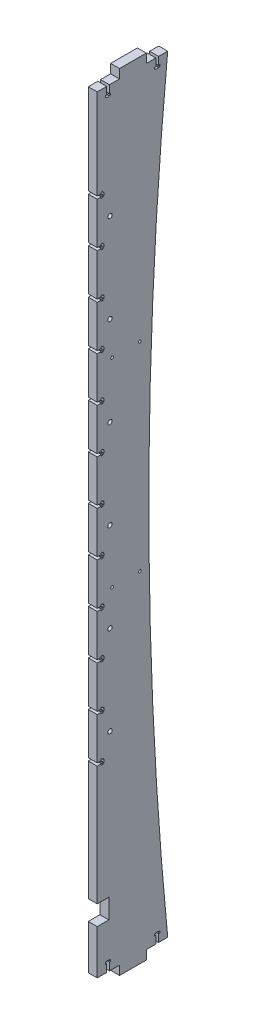
SolidWorks part; units mm, degrees
ref_plane "Płaszczyzna przednia" through (0, 0, 0) normal (0, 0, 1) x (1, 0, 0)
ref_plane "Płaszczyzna górna" through (0, 0, 0) normal (0, 1, 0) x (1, 0, 0)
ref_plane "Płaszczyzna prawa" through (0, 0, 0) normal (1, 0, 0) x (0, 0, -1)
ref_plane "Płaszczyzna2" through (248.5228, 0, 0) normal (-1, 0, 0) x (0, 0, 1)
sketch "Szkic11" plane through (248.5228, 0, 0) normal (-1, 0, 0) x (0, 0, 1)
  line L0 (-79.0014, 0) -> (0, 0)
  line L1 (0, 880) -> (-78.9552, 880)
  line L2 (-78.9552, 870) -> (-78.9552, 880)
  line L4 (-79.0014, 10) -> (-79.0014, 0)
  line L13 (0, 0) -> (0, 880)
  arc A2 (-79.0014, 10) -> (-78.9552, 870) centre (-4437.8003, 440.2341) ccw
extrude "Dodanie-wyciągnięcie1" add sketch "Szkic11" along normal blind 10
sketch "Szkic1" plane through (248.5228, 0, 0) normal (1, 0, 0) x (0, 0, -1)
  line L0 (85, 880) -> (85, 869.9)
  line L1 (85, 880) -> (55, 880)
  line L2 (85, 869.9) -> (55, 869.9)
  line L3 (55, 880) -> (55, 869.9)
  line L5 (25, 880) -> (25, 869.9)
  line L6 (25, 880) -> (0, 880)
  line L7 (25, 869.9) -> (0, 869.9)
  line L8 (0, 880) -> (0, 869.9)
  line L9 (0, 880) -> (78.9552, 880) construction
  dimension "D1" = 25
  dimension "D2" = 30
  dimension "D3" = 30
  dimension "D4" = 10.1
  dimension "D5" = 10.1
  dimension "D6" = 0
extrude "Wytnij-wyciągnięcie1" cut sketch "Szkic1" against normal blind 10
sketch "Szkic2" plane through (248.5228, 0, 0) normal (1, 0, 0) x (0, 0, -1)
  line L0 (10.6609, 869.9) -> (13.7609, 869.9)
  line L1 (10.6609, 869.9) -> (10.6609, 861.4)
  line L2 (13.7609, 869.9) -> (13.7609, 861.4)
  line L3 (10.6609, 858.9) -> (13.7609, 858.9)
  line L5 (9.2859, 859.4) -> (10.6609, 859.4)
  line L6 (9.2859, 859.4) -> (9.2859, 861.4)
  line L7 (15.1359, 859.4) -> (15.1359, 861.4)
  line L8 (9.2859, 861.4) -> (10.6609, 861.4)
  line L9 (13.7609, 859.4) -> (15.1359, 859.4)
  line L10 (10.6609, 859.4) -> (10.6609, 858.9)
  line L11 (13.7609, 859.4) -> (13.7609, 858.9)
  line L12 (13.7609, 861.4) -> (15.1359, 861.4)
  line L13 (0, 869.9) -> (25, 869.9) construction
  dimension "D1" = 11
  dimension "D2" = 5.85
  dimension "D3" = 3.1
  dimension "D4" = 1.375
  dimension "D5" = 2
  dimension "D6" = 0.5
  dimension "D7" = 0
extrude "Wytnij-wyciągnięcie2" cut sketch "Szkic2" against normal blind 10
pattern_linear "Szyk liniowy1" count 2 spacing 55 along (0, 0, -1) of "Wytnij-wyciągnięcie2"
ref_plane "Płaszczyzna1" through (0, 440, 0) normal (0, 1, 0) x (1, 0, 0)
sketch "Szkic6" plane through (248.5228, 0, 0) normal (1, 0, 0) x (0, 0, -1)
  line L1 (0, 765.69) -> (4.5, 765.69)
  line L2 (0, 765.69) -> (0, 768.79)
  line L3 (0, 768.79) -> (4.5, 768.79)
  line L4 (7.5, 765.69) -> (7.5, 768.79)
  line L5 (6.5, 765.69) -> (7.5, 765.69)
  line L6 (4.5, 764.315) -> (6.5, 764.315)
  line L7 (4.5, 764.315) -> (4.5, 765.69)
  line L8 (4.5, 770.165) -> (6.5, 770.165)
  line L9 (6.5, 764.315) -> (6.5, 765.69)
  line L10 (4.5, 768.79) -> (4.5, 770.165)
  line L11 (6.5, 768.79) -> (7.5, 768.79)
  line L12 (6.5, 768.79) -> (6.5, 770.165)
  line L14 (0, 869.9) -> (10.6609, 869.9) construction
  point P14 (0, 767.24)
  dimension "D1" = 7.5
  dimension "D2" = 1
  dimension "D3" = 2
  dimension "D4" = 5.85
  dimension "D5" = 1.375
  dimension "D6" = 3.1
  dimension "D7" = 102.66
extrude "Wytnij-wyciągnięcie4" cut sketch "Szkic6" against normal blind 10
pattern_linear "Szyk liniowy2" count 12 spacing 50 along (0, -1, 0) of "Wytnij-wyciągnięcie4"
sketch "Szkic7" plane through (248.5228, 0, 0) normal (1, 0, 0) x (0, 0, -1)
  circle A0 centre (14.3107, 742.237) radius 2.45
  circle A2 centre (14.3107, 742.237) radius 3.2 construction
  circle A3 centre (14.3107, 742.237) radius 3.2
  dimension "D1" = 4.9
sketch "Szkic14" plane through (238.5228, 0, 0) normal (-1, 0, 0) x (0, 0, 1)
  circle A0 centre (-14.3107, 742.237) radius 2.45 construction
  circle A1 centre (-14.3107, 742.237) radius 2.45
extrude "Wytnij-wyciągnięcie8" cut sketch "Szkic14" against normal blind 10
sketch "Szkic8" plane through (248.5228, 0, 0) normal (1, 0, 0) x (0, 0, -1)
  line L3 (13, 60) -> (13, 82)
  line L4 (0, 60) -> (13, 60)
  line L5 (13, 82) -> (0, 82)
  line L6 (0, 60) -> (0, 82)
extrude "Wytnij-wyciągnięcie6" cut sketch "Szkic8" against normal blind 10
mirror "Lustro1" about plane through (0, 440, 0) normal (0, 1, 0) of "Szyk liniowy1", "Wytnij-wyciągnięcie2", "Wytnij-wyciągnięcie1"
sketch "Szkic12" plane through (248.5228, 0, 0) normal (1, 0, 0) x (0, 0, -1)
  line L0 (15.15, 377.737) -> (15.15, 383.737) construction
  line L1 (18.25, 377.737) -> (18.25, 383.737) construction
  line L2 (46.15, 377.737) -> (46.15, 383.737) construction
  line L3 (49.25, 377.737) -> (49.25, 383.737) construction
  line L4 (15.15, 377.737) -> (15.15, 383.737)
  line L5 (18.25, 377.737) -> (18.25, 383.737)
  line L6 (46.15, 377.737) -> (46.15, 383.737)
  line L7 (49.25, 377.737) -> (49.25, 383.737)
  line L8 (15.15, 380.737) -> (18.25, 380.737)
  line L9 (46.15, 380.737) -> (49.25, 380.737)
  circle A0 centre (16.7, 380.737) radius 1.55
  circle A1 centre (47.7, 380.737) radius 1.55
  dimension "D1" = 3.1
  dimension "D2" = 3.1
sketch "Szkic13" plane through (248.5228, 0, 0) normal (1, 0, 0) x (0, 0, -1)
  circle A0 centre (16.7, 380.737) radius 1.55 construction
  circle A1 centre (47.7, 380.737) radius 1.55 construction
  circle A2 centre (16.7, 380.737) radius 1.55
  circle A3 centre (47.7, 380.737) radius 1.55
extrude "Wytnij-wyciągnięcie7" cut sketch "Szkic13" against normal blind 10
pattern_linear "Szyk liniowy4" count 2 spacing 223 along (0, 1, 0) of "Wytnij-wyciągnięcie7"
pattern_linear "Szyk liniowy5" count 6 spacing 100 along (0, -1, 0) of "Wytnij-wyciągnięcie8"
equation "\"tolerancja_wpusy\"=0.2"
equation "\"dlugosc_wpustu_duzy\"=20"
equation "\"srednica_otworu_M3\"=3.1"
equation "\"szerokosc_nogi_T\"=3.1"
equation "\"dlugosc_T_30\"=11"
equation "\"grubosc_na_nakretke_kwadrat\"=2"
equation "\"szerokosc_na_nakretke_kwadrat\"=5.85"
equation "\"wyokosc_nadstawki_T\"=0.5"
equation "\"D1@Szkic2\"=\"dlugosc_T_30\""
equation "\"D2@Szkic2\"=\"szerokosc_na_nakretke_kwadrat\""
equation "\"D3@Szkic2\"=\"szerokosc_nogi_T\""
equation "\"D4@Szkic2\"=(\"szerokosc_na_nakretke_kwadrat\"-\"szerokosc_nogi_T\")/2"
equation "\"D5@Szkic2\"=\"grubosc_na_nakretke_kwadrat\""
equation "\"D6@Szkic2\"=\"wyokosc_nadstawki_T\""
equation "\"D3@Szkic6\" = \"grubosc_na_nakretke_kwadrat\""
equation "\"D4@Szkic6\"=\"szerokosc_na_nakretke_kwadrat\""
equation "\"D5@Szkic6\"=(\"szerokosc_na_nakretke_kwadrat\"-\"szerokosc_nogi_T\")/2"
equation "\"D6@Szkic6\"=\"szerokosc_nogi_T\""
equation "\"D1@Szkic12\"=\"srednica_otworu_M3\""
